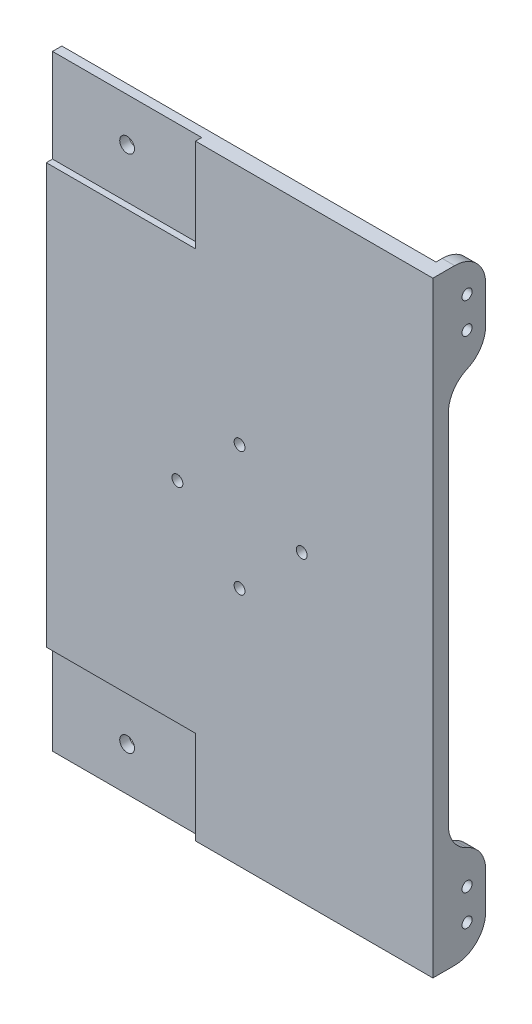
SolidWorks part; units mm, degrees
ref_plane "Alzado" through (0, 0, 0) normal (0, 0, 1) x (1, 0, 0)
ref_plane "Planta" through (0, 0, 0) normal (0, 1, 0) x (1, 0, 0)
ref_plane "Vista lateral" through (0, 0, 0) normal (1, 0, 0) x (0, 0, -1)
sketch "Croquis1" plane through (0, 0, 0) normal (0, 0, 1) x (1, 0, 0)
  line L1 (-117.2917, 97.7627) -> (131.4683, 97.7627)
  line L2 (-117.2917, 97.7627) -> (-117.2917, -97.2373)
  line L3 (-117.2917, -97.2373) -> (131.4683, -97.2373)
  line L4 (131.4683, 97.7627) -> (131.4683, -97.2373)
  dimension "D1" = 248.76
  dimension "D2" = 195
extrude "Saliente-Extruir1" add sketch "Croquis1" along normal blind 5
sketch "Croquis2" plane through (0, 0, 5) normal (0, 0, 1) x (1, 0, 0)
  line L0 (-117.2917, 0.2627) -> (131.4683, 0.2627) construction
  line L1 (-117.2917, 97.7627) -> (-117.2917, -97.2373) construction
  line L2 (131.4683, -97.2373) -> (131.4683, 97.7627) construction
  line L3 (-117.2917, -97.2373) -> (-69.2917, -97.2373)
  line L4 (-117.2917, -97.2373) -> (131.4683, -97.2373) construction
  line L5 (-69.2917, -97.2373) -> (-69.2917, -67.2373)
  line L6 (-69.2917, -67.2373) -> (-117.2917, -67.2373)
  line L7 (-117.2917, -67.2373) -> (-117.2917, -97.2373)
  line L8 (131.4683, 67.7627) -> (101.4683, 67.7627)
  line L9 (131.4683, -97.2373) -> (101.4683, -97.2373)
  line L10 (131.4683, -97.2373) -> (131.4683, -67.2373)
  line L11 (131.4683, -67.2373) -> (101.4683, -67.2373)
  line L12 (101.4683, -97.2373) -> (101.4683, -67.2373)
  line L13 (101.4683, 97.7627) -> (101.4683, 67.7627)
  line L14 (131.4683, 97.7627) -> (101.4683, 97.7627)
  line L15 (131.4683, 97.7627) -> (131.4683, 67.7627)
  line L16 (-69.2917, 67.7627) -> (-117.2917, 67.7627)
  line L17 (-69.2917, 97.7627) -> (-69.2917, 67.7627)
  line L18 (-117.2917, 97.7627) -> (-69.2917, 97.7627)
  line L19 (-117.2917, 67.7627) -> (-117.2917, 97.7627)
  dimension "D1" = 48
  dimension "D2" = 30
  dimension "D3" = 30
  dimension "D4" = 30
extrude "Cortar-Extruir1" cut sketch "Croquis2" against normal blind 2
sketch "Croquis3" plane through (0, 0, 5) normal (0, 0, 1) x (1, 0, 0)
  line L0 (-69.2917, 97.7627) -> (-117.2917, 97.7627) construction
  line L1 (116.4683, 83.7627) -> (116.4683, 67.7627) construction
  line L3 (116.4683, -83.2373) -> (116.4683, -67.2373) construction
  line L5 (131.4683, -67.2373) -> (101.4683, -67.2373) construction
  line L6 (101.4683, 67.7627) -> (131.4683, 67.7627) construction
  line L7 (-93.2917, 83.7627) -> (-93.2917, 67.7627) construction
  line L8 (-117.2917, 67.7627) -> (-69.2917, 67.7627) construction
  line L9 (-93.2917, -83.2373) -> (-93.2917, -67.2373) construction
  line L10 (-69.2917, -67.2373) -> (-117.2917, -67.2373) construction
  circle A0 centre (-93.2917, 83.7627) radius 2.375
  circle A1 centre (-93.2917, -83.2373) radius 2.375
  circle A2 centre (116.4683, 83.7627) radius 2.375
  circle A3 centre (116.4683, -83.2373) radius 2.375
  dimension "D2" = 4.75
  dimension "D3" = 4.75
  dimension "D5" = 4.75
  dimension "D6" = 4.75
  dimension "D1" = 14
  dimension "D4" = 14
  dimension "D7" = 209.76
  dimension "D8" = 16
  dimension "D9" = 16
extrude "Cortar-Extruir2" cut sketch "Croquis3" against normal blind 10
sketch "Croquis4" plane through (0, 0, 0) normal (0, 0, -1) x (-1, 0, 0)
  line L7 (-131.4683, 97.7627) -> (117.2917, 97.7627) construction
  line L9 (117.2917, 97.7627) -> (117.2917, -97.2373) construction
  circle A0 centre (55.1017, 0.2627) radius 40
  dimension "D3" = 80
  dimension "D1" = 62.19
  dimension "D2" = 97.5
extrude "Saliente-Extruir2" add sketch "Croquis4" along normal blind 206 contours A0
sketch "Croquis5" plane through (0, 0, 0) normal (0, 0, -1) x (-1, 0, 0)
  line L0 (-131.4683, 0.2627) -> (117.2917, 0.2627) construction
  line L1 (-131.4683, -97.2373) -> (-131.4683, 97.7627) construction
  line L2 (117.2917, 97.7627) -> (117.2917, -97.2373) construction
  circle A0 centre (-76.9683, 0.2627) radius 12.5
  dimension "D1" = 25
  dimension "D2" = 54.5
extrude "Cortar-Extruir3" cut sketch "Croquis5" against normal blind 10
sketch "Croquis6" plane through (0, 0, 0) normal (0, 0, -1) x (-1, 0, 0)
  line L0 (-131.4683, 97.7627) -> (117.2917, 97.7627) construction
  line L1 (-7.0883, 97.7627) -> (-7.0883, -97.2373)
  line L2 (117.2917, -97.2373) -> (-131.4683, -97.2373) construction
  line L3 (-7.0883, 97.7627) -> (117.2917, 97.7627)
  line L4 (117.2917, 97.7627) -> (117.2917, -97.2373)
  line L5 (117.2917, -97.2373) -> (-7.0883, -97.2373)
  line L6 (-131.4683, 0.2627) -> (56.0317, 0.2627)
  line L7 (-131.4683, -97.2373) -> (-131.4683, 97.7627) construction
  circle A1 centre (56.0317, 0.2627) radius 100
  dimension "D1" = 200
  dimension "D2" = 187.5
sketch "Croquis9" plane through (0, 97.7627, 0) normal (0, 1, 0) x (1, 0, 0)
  line L0 (7.0883, 0) -> (7.0883, -5)
  line L1 (131.4683, 0) -> (-117.2917, 0) construction
  line L2 (101.4683, -5) -> (-69.2917, -5) construction
ref_plane "Plano3" through (7.0883, 0, 0) normal (1, 0, 0) x (0, 0, -1)
sketch "Croquis12" plane through (7.0883, 0, 0) normal (1, 0, 0) x (0, 0, -1)
  line L0 (0, 97.7627) -> (0, 67.7627)
  line L1 (0, 67.7627) -> (12, 67.7627)
  line L2 (12, 67.7627) -> (12, 97.7627)
  line L3 (12, 97.7627) -> (0, 97.7627)
  line L4 (0, -97.2373) -> (12, -97.2373)
  line L5 (12, -97.2373) -> (12, -67.2373)
  line L6 (12, -67.2373) -> (0, -67.2373)
  line L7 (0, -67.2373) -> (0, -97.2373)
  dimension "D1" = 30
  dimension "D2" = 12
  dimension "D3" = 30
  dimension "D4" = 12
extrude "Saliente-Extruir3" add sketch "Croquis12" along normal mid plane 8
fillet "Redondeo1" radius 10 2 edges at (7.0883, -67.2373, 0) (7.0883, 67.7627, 0)
fillet "Redondeo2" radius 10 2 edges at (7.0883, 67.7627, -12) (7.0883, -67.2373, -12)
fillet "Redondeo3" radius 10 2 edges at (7.0883, -97.2373, -12) (7.0883, 97.7627, -12)
sketch "Croquis13" plane through (11.0883, 0, 0) normal (1, 0, 0) x (0, 0, -1)
  line L0 (-5, 0.2627) -> (206, 0.2627) construction
  line L1 (-5, -67.2373) -> (-5, 67.7627) construction
  line L2 (206, -39.7373) -> (206, 40.2627) construction
  line L3 (6, 87.7627) -> (12, 87.7627) construction
  line L4 (6, 87.7627) -> (6, 77.7627) construction
  circle A0 centre (6, 87.7627) radius 1.625
  circle A1 centre (6, 77.7627) radius 1.625
  circle A2 centre (6, -77.2373) radius 1.625
  circle A3 centre (6, -87.2373) radius 1.625
  dimension "D3" = 3.25
  dimension "D4" = 3.25
  dimension "D1" = 6
extrude "Cortar-Extruir5" cut sketch "Croquis13" against normal through all both and the other way through all
sketch "Croquis14" plane through (0, 0, 0) normal (0, 0, -1) x (-1, 0, 0)
  line L0 (-7.0883, 97.7627) -> (-7.0883, -97.2373)
  line L1 (-7.0883, 97.7627) -> (117.2917, 97.7627)
  line L2 (117.2917, 97.7627) -> (117.2917, -97.2373)
  line L3 (117.2917, -97.2373) -> (-7.0883, -97.2373)
sketch "Croquis15" plane through (0, 0, 5) normal (0, 0, 1) x (1, 0, 0)
  line L0 (111.4683, 67.7627) -> (131.4683, 67.7627)
  line L1 (111.4683, 67.7627) -> (111.4683, 60.0127)
  line L2 (131.4683, -67.2373) -> (101.4683, -67.2373) construction
  line L3 (111.4683, -67.2373) -> (111.4683, -59.4873)
  line L4 (111.4683, -59.4873) -> (125.2183, -59.4873)
  line L5 (125.2183, -59.4873) -> (125.2183, 60.0127)
  line L6 (111.4683, 60.0127) -> (125.2183, 60.0127)
  line L7 (111.4683, -67.2373) -> (131.4683, -67.2373)
  line L10 (131.4683, -67.2373) -> (131.4683, 67.7627)
  dimension "D1" = 119.5
  dimension "D2" = 7.75
  dimension "D3" = 13.75
extrude "Cortar-Extruir7" cut sketch "Croquis15" against normal blind 2
sketch "Croquis16" plane through (0, 0, 5) normal (0, 0, 1) x (1, 0, 0)
  circle A1 centre (-55.1017, 20.2627) radius 1.75
  circle A2 centre (-35.1017, 0.2627) radius 1.75
  circle A3 centre (-55.1017, -19.7373) radius 1.75
  circle A4 centre (-75.1017, 0.2627) radius 1.75
  dimension "D3" = 3.5
  dimension "D4" = 4
extrude "Cortar-Extruir9" cut sketch "Croquis16" against normal blind 20
sketch "Croquis17" plane through (0, -97.2373, 0) normal (0, -1, 0) x (1, 0, 0)
  line L0 (-117.2917, 0) -> (3.0883, 0)
  line L1 (3.0883, 0) -> (3.0883, -213.2128)
  line L2 (3.0883, -213.2128) -> (-117.2917, -213.2128)
  line L3 (-117.2917, 0) -> (-117.2917, -213.2128)
extrude "Cortar-Extruir10" cut sketch "Croquis17" against normal blind 222
sketch "Croquis18" plane through (0, 0, 0) normal (0, 0, -1) x (-1, 0, 0)
  line L0 (-7.0883, 97.7627) -> (-7.0883, -97.2373)
  line L1 (-7.0883, -97.2373) -> (-131.4683, -97.2373)
  line L2 (-131.4683, -97.2373) -> (-131.4683, 97.7627)
  line L3 (-131.4683, 97.7627) -> (-7.0883, 97.7627)
extrude "Cortar-Extruir14" cut sketch "Croquis18" against normal through all both and the other way through all
